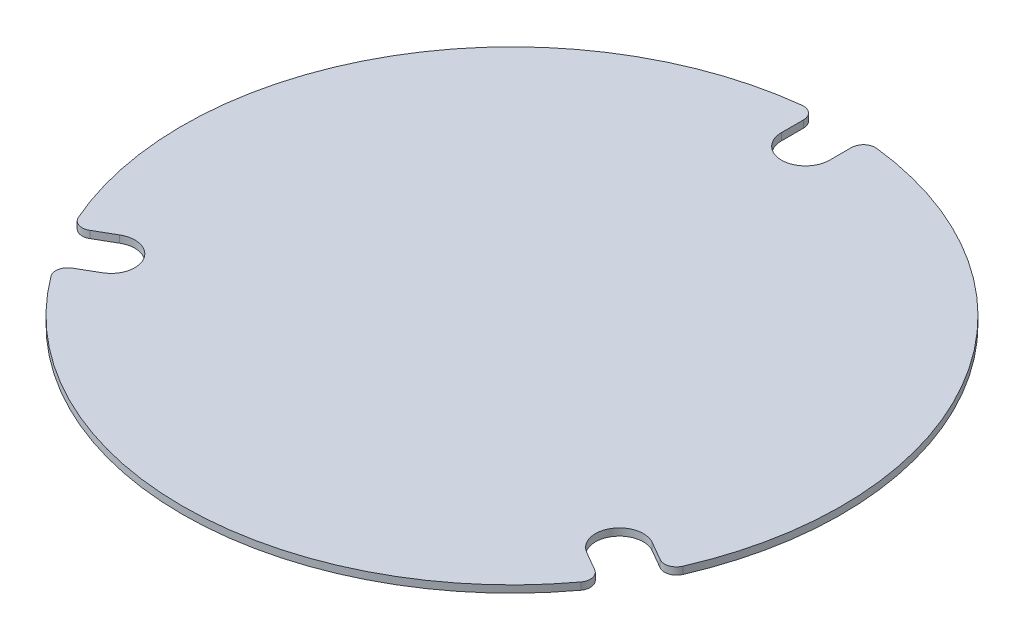
SolidWorks part; units mm, degrees
ref_plane "Front Plane" through (0, 0, 0) normal (0, 0, 1) x (1, 0, 0)
ref_plane "Top Plane" through (0, 0, 0) normal (0, 1, 0) x (1, 0, 0)
ref_plane "Right Plane" through (0, 0, 0) normal (1, 0, 0) x (0, 0, -1)
sketch "Sketch2" plane through (0, 0, 0) normal (0, 1, 0) x (1, 0, 0)
  line L0 (-4, 52.6593) -> (-4, 49)
  line L1 (-4, 49) -> (4, 49) construction
  line L2 (4, 49) -> (4, 52.6593)
  line L3 (0, 49) -> (0, 55) construction
  line L4 (47.6043, -22.8655) -> (44.4352, -21.0359)
  line L5 (40.4352, -27.9641) -> (43.6043, -29.7937)
  line L6 (-43.6043, -29.7937) -> (-40.4352, -27.9641)
  line L7 (-44.4352, -21.0359) -> (-47.6043, -22.8655)
  line L8 (0, 0) -> (0, 49) construction
  line L9 (0, 0) -> (42.4352, -24.5) construction
  arc A0 (-6.2264, 54.6464) -> (-50.4384, -21.931) centre (0, 0) ccw
  arc A1 (-4, 49) -> (4, 49) centre (0, 49) ccw
  arc A2 (-4, 54.8544) -> (4, 54.8544) centre (0, 0) cw construction
  arc A3 (44.4352, -21.0359) -> (40.4352, -27.9641) centre (42.4352, -24.5) ccw
  arc A4 (-40.4352, -27.9641) -> (-44.4352, -21.0359) centre (-42.4352, -24.5) ccw
  arc A5 (50.4384, -21.931) -> (6.2264, 54.6464) centre (0, 0) ccw
  arc A6 (-44.212, -32.7154) -> (44.212, -32.7154) centre (0, 0) ccw
  arc A7 (-44.212, -32.7154) -> (-43.6043, -29.7937) centre (-42.6043, -31.5258) cw
  arc A8 (-47.6043, -22.8655) -> (-50.4384, -21.931) centre (-48.6043, -21.1335) cw
  arc A9 (50.4384, -21.931) -> (47.6043, -22.8655) centre (48.6043, -21.1335) cw
  arc A10 (44.212, -32.7154) -> (43.6043, -29.7937) centre (42.6043, -31.5258) ccw
  arc A11 (6.2264, 54.6464) -> (4, 52.6593) centre (6, 52.6593) ccw
  arc A12 (-4, 52.6593) -> (-6.2264, 54.6464) centre (-6, 52.6593) ccw
  dimension "D1" = 110
  dimension "D2" = 4
  dimension "D6" = 2
  dimension "D3" = 6
  dimension "D5" = 120
  dimension "D4" = 3
extrude "Boss-Extrude1" add sketch "Sketch2" along normal blind 1.2 contours A0 A8 L7 A4 L6 A7 A6 A10 L5 A3 L4 A9 A5 A11 L2 A1 L0 A12
sketch "Sketch3" plane through (0, 0, 0) normal (0, -1, 0) x (1, 0, 0)
  line L18 (-5.85, -52.6593) -> (-5.85, -49)
  line L19 (5.85, -49) -> (5.85, -52.6593)
  line L20 (48.5293, 21.2634) -> (45.3602, 19.4338)
  line L21 (39.5102, 29.5662) -> (42.6793, 31.3959)
  line L22 (-42.6793, 31.3959) -> (-39.5102, 29.5662)
  line L23 (-45.3602, 19.4338) -> (-48.5293, 21.2634)
  line L24 (-5.85, -52.6593) -> (-5.85, -49)
  line L25 (5.85, -49) -> (5.85, -52.6593)
  line L26 (48.5293, 21.2634) -> (45.3602, 19.4338)
  line L27 (39.5102, 29.5662) -> (42.6793, 31.3959)
  line L28 (-42.6793, 31.3959) -> (-39.5102, 29.5662)
  line L29 (-45.3602, 19.4338) -> (-48.5293, 21.2634)
  arc A36 (-6.017, -52.8083) -> (-5.85, -52.6593) centre (-6, -52.6593) ccw
  arc A37 (5.85, -49) -> (-5.85, -49) centre (0, -49) ccw
  arc A38 (5.85, -52.6593) -> (6.017, -52.8083) centre (6, -52.6593) ccw
  arc A39 (6.017, -52.8083) -> (48.7418, 21.1933) centre (0, 0) ccw
  arc A40 (48.7418, 21.1933) -> (48.5293, 21.2634) centre (48.6043, 21.1335) ccw
  arc A41 (39.5102, 29.5662) -> (45.3602, 19.4338) centre (42.4352, 24.5) ccw
  arc A42 (42.6793, 31.3959) -> (42.7249, 31.615) centre (42.6043, 31.5258) ccw
  arc A43 (42.7249, 31.615) -> (-42.7249, 31.615) centre (0, 0) ccw
  arc A44 (-42.7249, 31.615) -> (-42.6793, 31.3959) centre (-42.6043, 31.5258) ccw
  arc A45 (-45.3602, 19.4338) -> (-39.5102, 29.5662) centre (-42.4352, 24.5) ccw
  arc A46 (-48.5293, 21.2634) -> (-48.7418, 21.1933) centre (-48.6043, 21.1335) ccw
  arc A47 (-48.7418, 21.1933) -> (-6.017, -52.8083) centre (0, 0) ccw
  arc A48 (-6.017, -52.8083) -> (-5.85, -52.6593) centre (-6, -52.6593) ccw
  arc A49 (5.85, -49) -> (-5.85, -49) centre (0, -49) ccw
  arc A50 (5.85, -52.6593) -> (6.017, -52.8083) centre (6, -52.6593) ccw
  arc A51 (6.017, -52.8083) -> (48.7418, 21.1933) centre (0, 0) ccw
  arc A52 (48.7418, 21.1933) -> (48.5293, 21.2634) centre (48.6043, 21.1335) ccw
  arc A53 (39.5102, 29.5662) -> (45.3602, 19.4338) centre (42.4352, 24.5) ccw
  arc A54 (42.6793, 31.3959) -> (42.7249, 31.615) centre (42.6043, 31.5258) ccw
  arc A55 (42.7249, 31.615) -> (-42.7249, 31.615) centre (0, 0) ccw
  arc A56 (-42.7249, 31.615) -> (-42.6793, 31.3959) centre (-42.6043, 31.5258) ccw
  arc A57 (-45.3602, 19.4338) -> (-39.5102, 29.5662) centre (-42.4352, 24.5) ccw
  arc A58 (-48.5293, 21.2634) -> (-48.7418, 21.1933) centre (-48.6043, 21.1335) ccw
  arc A59 (-48.7418, 21.1933) -> (-6.017, -52.8083) centre (0, 0) ccw
  dimension "D1" = 1.85
extrude "Extrude-Thin1" add sketch "Sketch3" along normal blind 1.2 thin
